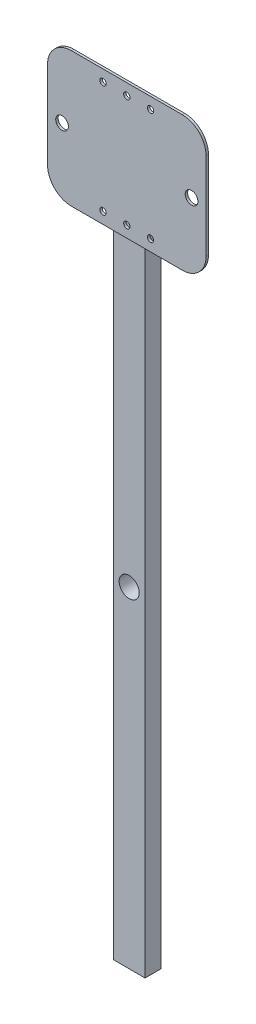
SolidWorks part; units mm, degrees
ref_plane "Alzado" through (0, 0, 0) normal (0, 0, 1) x (1, 0, 0)
ref_plane "Planta" through (0, 0, 0) normal (0, 1, 0) x (1, 0, 0)
ref_plane "Vista lateral" through (0, 0, 0) normal (1, 0, 0) x (0, 0, -1)
sketch "Croquis1" plane through (0, 0, 0) normal (0, 0, 1) x (1, 0, 0)
  line L1 (70, 85) -> (-70, 85)
  line L2 (100, 55) -> (100, -55)
  line L3 (70, -85) -> (-70, -85)
  line L4 (-100, 55) -> (-100, -55)
  circle A0 centre (-81.705, 0) radius 8
  circle A1 centre (81.705, 0) radius 8
  circle A2 centre (0, 70.6) radius 4
  circle A3 centre (0, -70.6) radius 4
  circle A4 centre (-30, 70.6) radius 4
  circle A5 centre (30, 70.6) radius 4
  circle A6 centre (-30, -70.6) radius 4
  circle A7 centre (30, -70.6) radius 4
  arc A8 (-100, -55) -> (-70, -85) centre (-70, -55) ccw
  arc A9 (70, -85) -> (100, -55) centre (70, -55) ccw
  arc A10 (100, 55) -> (70, 85) centre (70, 55) ccw
  arc A11 (-70, 85) -> (-100, 55) centre (-70, 55) ccw
extrude "Saliente-Extruir1" add sketch "Croquis1" along normal blind 3
sketch "Croquis2" plane through (0, 0, 0) normal (0, 0, 1) x (1, 0, 0)
  line L0 (-20, 0) -> (20, 0)
  line L3 (-20, 0) -> (-20, -885)
  line L4 (-20, -885) -> (20, -885)
  line L5 (20, 0) -> (20, -885)
  circle A0 centre (0, -467.75) radius 12.7
extrude "Saliente-Extruir2" add sketch "Croquis2" against normal blind 20
